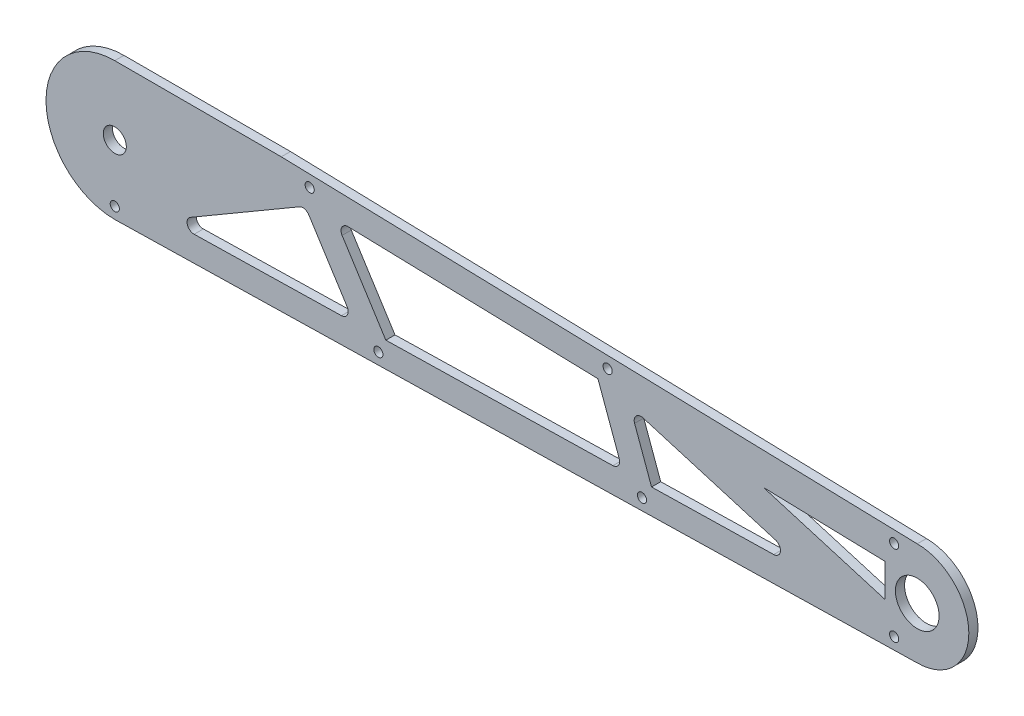
SolidWorks part; units mm, degrees
ref_plane "前视基准面" through (0, 0, 0) normal (0, 0, 1) x (1, 0, 0)
ref_plane "上视基准面" through (0, 0, 0) normal (0, 1, 0) x (1, 0, 0)
ref_plane "右视基准面" through (0, 0, 0) normal (1, 0, 0) x (0, 0, -1)
sketch "草图1" plane through (0, 0, 0) normal (0, 0, 1) x (1, 0, 0)
  line L1 (-1.4571, -0.1457) -> (348.5429, -0.1457) construction
  line L4 (348.5429, 22.3543) -> (71.1533, 29.8543)
  line L8 (-1.4571, -30.1457) -> (348.5429, -22.6457)
  line L10 (-1.4571, -30.1457) -> (-1.4571, -25.1457) construction
  line L11 (71.1533, 29.8543) -> (-1.4571, 29.8543)
  circle A1 centre (-1.4571, -0.1457) radius 5.03
  circle A4 centre (-1.4571, -0.1457) radius 30 construction
  circle A11 centre (348.5429, -0.1457) radius 9.53
  circle A14 centre (348.5429, -0.1457) radius 22.5 construction
  arc A17 (-1.4571, -30.1457) -> (-1.4571, 29.8543) centre (-1.4571, -0.1457) cw
  arc A20 (348.5429, -22.6457) -> (348.5429, 22.3543) centre (348.5429, -0.1457) ccw
  circle A21 centre (-1.4571, -25.1457) radius 2
  circle A28 centre (83.5587, 24.4904) radius 2
  circle A29 centre (213.5112, 20.9768) radius 2
  circle A30 centre (343.4637, 17.4631) radius 2 construction
  circle A31 centre (343.4637, -17.7546) radius 2 construction
  circle A32 centre (228.4901, -20.2183) radius 2
  circle A33 centre (113.5165, -22.682) radius 2
  circle A41 centre (338.4637, -17.7546) radius 2
  circle A43 centre (338.4637, 17.4631) radius 2
  dimension "D1" = 350
  dimension "D2" = 10.06
  dimension "D3" = 45
  dimension "D4" = 19.06
  dimension "D5" = 5
  dimension "D6" = 5
extrude "凸台-拉伸1" add sketch "草图1" along normal blind 4
sketch "草图4" plane through (0, 0, 0) normal (0, 0, -1) x (-1, 0, 0)
  line L0 (1.4571, -25.1457) -> (-113.5165, -22.682) construction
  line L1 (-113.5165, -22.682) -> (-83.5587, 24.4904) construction
  line L2 (-83.5587, 24.4904) -> (1.4571, -25.1457) construction
  line L3 (-79.0966, 14.9375) -> (-31.5664, -12.8128)
  line L4 (-33.1433, -18.4029) -> (-97.4221, -17.0255)
  line L5 (-99.8903, -12.4179) -> (-83.1417, 13.955)
  line L6 (-113.5165, -22.682) -> (-228.4901, -20.2183) construction
  line L7 (-228.4901, -20.2183) -> (-213.5112, 20.9768) construction
  line L8 (-213.5112, 20.9768) -> (-83.5587, 24.4904) construction
  line L9 (-116.7686, -16.6109) -> (-215.804, -14.4887)
  line L10 (-218.5591, -10.4643) -> (-209.2676, 15.0893)
  line L11 (-209.2676, 15.0893) -> (-100.3052, 18.0354)
  line L12 (-116.7686, -16.6109) -> (-97.6916, 13.4282)
  line L13 (-228.4901, -20.2183) -> (-343.4637, -17.7546) construction
  line L14 (-343.4637, -17.7546) -> (-213.5112, 20.9768) construction
  line L15 (-232.6597, -14.1275) -> (-285.9537, -12.9855)
  line L16 (-286.7463, -7.1112) -> (-228.9383, 10.118)
  line L17 (-232.6597, -14.1275) -> (-225.262, 6.2178)
  line L18 (-213.5112, 20.9768) -> (-343.4637, 17.4631) construction
  line L19 (-343.4637, 17.4631) -> (-343.4637, -17.7546) construction
  line L20 (-334.4637, -5.6809) -> (-281.3866, 10.1383)
  line L21 (-281.3866, 10.1383) -> (-334.4637, 8.7032)
  line L22 (-334.4637, 8.7032) -> (-334.4637, -5.6809)
  arc A0 (-286.7463, -7.1112) -> (-285.9537, -12.9855) centre (-285.8894, -9.9862) ccw
  arc A1 (-228.9383, 10.118) -> (-225.262, 6.2178) centre (-228.0814, 7.243) cw
  arc A2 (-218.5591, -10.4643) -> (-215.804, -14.4887) centre (-215.7397, -11.4894) ccw
  arc A3 (-100.3052, 18.0354) -> (-97.6916, 13.4282) centre (-100.2241, 15.0365) cw
  arc A4 (-99.8903, -12.4179) -> (-97.4221, -17.0255) centre (-97.3579, -14.0262) ccw
  arc A5 (-83.1417, 13.955) -> (-79.0966, 14.9375) centre (-80.6092, 12.3467) cw
  arc A6 (-33.1433, -18.4029) -> (-31.5664, -12.8128) centre (-33.079, -15.4036) ccw
  dimension "D1" = 3
extrude "切除-拉伸1" cut sketch "草图4" against normal blind 10
